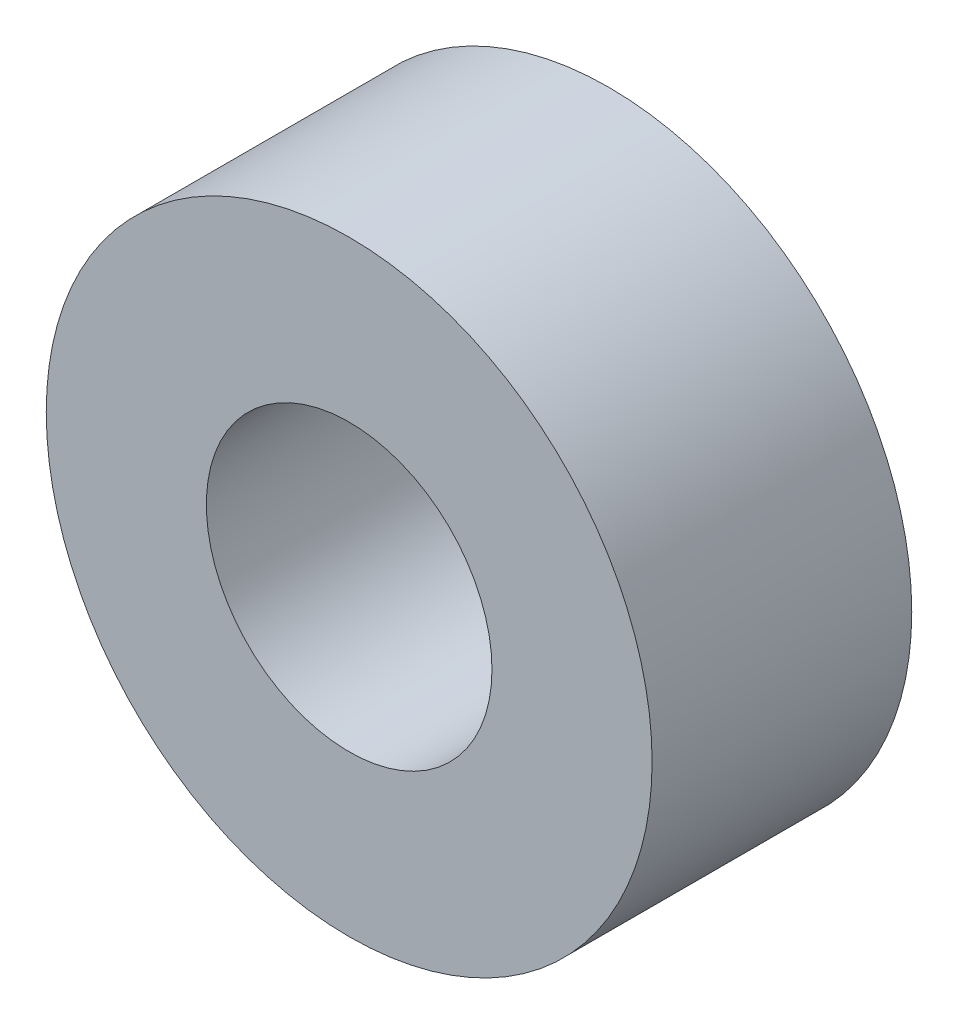
SolidWorks part; units mm, degrees
ref_plane "Front Plane" through (0, 0, 0) normal (1, 0, 0) x (0, 1, 0)
ref_plane "Top Plane" through (0, 0, 0) normal (0, 0, 1) x (0, 1, 0)
ref_plane "Right Plane" through (0, 0, 0) normal (0, 1, 0) x (-1, 0, 0)
sketch "Sketch1" plane through (0, 0, 0) normal (0, 0, 1) x (0, 1, 0)
  circle A0 centre (0, 0) radius 3.5
  circle A1 centre (0, 0) radius 1.65
  dimension "D1" = 3.3
  dimension "D2" = 7
extrude "Boss-Extrude1" add sketch "Sketch1" along normal blind 3
